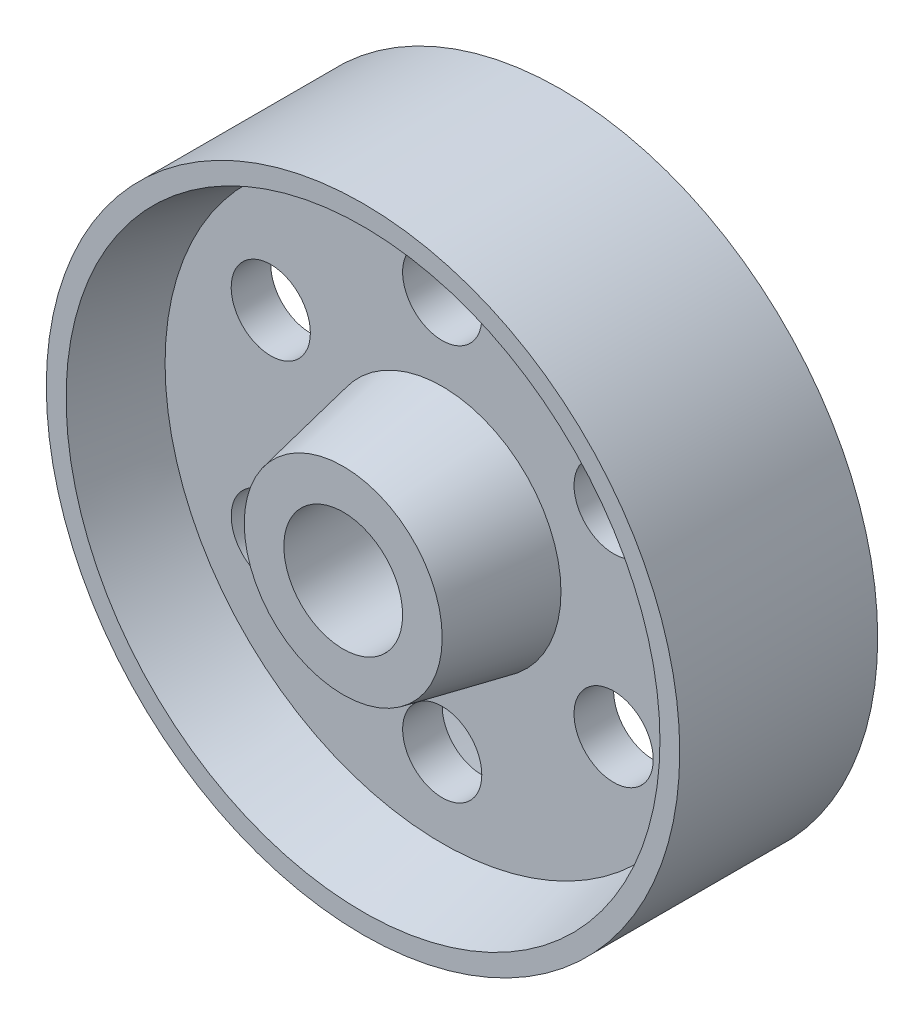
SolidWorks part; units mm, degrees
ref_plane "Front Plane" through (0, 0, 0) normal (0, 0, 1) x (1, 0, 0)
ref_plane "Top Plane" through (0, 0, 0) normal (0, 1, 0) x (1, 0, 0)
ref_plane "Right Plane" through (0, 0, 0) normal (1, 0, 0) x (0, 0, -1)
sketch "Sketch1" plane through (0, 0, 0) normal (1, 0, 0) x (0, 0, -1)
  line L0 (-37.3089, 0) -> (50.2315, 0) construction
  line L1 (0, -101.055) -> (0, 103.0597) construction
  line L2 (19.05, 9.525) -> (-19.05, 9.525)
  line L3 (-19.05, 9.525) -> (-19.05, 15.875)
  line L4 (-19.05, 15.875) -> (-3.175, 19.05)
  line L5 (-3.175, 19.05) -> (-3.175, 44.45)
  line L6 (-3.175, 44.45) -> (-15.875, 47.625)
  line L7 (-15.875, 47.625) -> (-15.875, 50.8)
  line L8 (-15.875, 50.8) -> (15.875, 50.8)
  line L9 (15.875, 47.625) -> (15.875, 50.8)
  line L10 (3.175, 44.45) -> (15.875, 47.625)
  line L11 (3.175, 19.05) -> (3.175, 44.45)
  line L12 (19.05, 15.875) -> (3.175, 19.05)
  line L13 (19.05, 9.525) -> (19.05, 15.875)
  line L14 (19.05, -9.525) -> (19.05, -15.875)
  line L15 (19.05, -15.875) -> (3.175, -19.05)
  line L16 (3.175, -19.05) -> (3.175, -44.45)
  line L17 (3.175, -44.45) -> (15.875, -47.625)
  line L18 (15.875, -47.625) -> (15.875, -50.8)
  line L19 (-15.875, -50.8) -> (15.875, -50.8)
  line L20 (-15.875, -47.625) -> (-15.875, -50.8)
  line L21 (-3.175, -44.45) -> (-15.875, -47.625)
  line L22 (-3.175, -19.05) -> (-3.175, -44.45)
  line L23 (-19.05, -15.875) -> (-3.175, -19.05)
  line L24 (-19.05, -9.525) -> (-19.05, -15.875)
  line L25 (19.05, -9.525) -> (-19.05, -9.525)
  point P14 (0, 50.8)
  point P19 (0, 9.525)
  point P31 (0, -9.525)
  point P32 (0, -50.8)
  dimension "D1" = 31.75
  dimension "D2" = 38.1
  dimension "D3" = 101.6
  dimension "D4" = 19.05
  dimension "D5" = 31.75
  dimension "D6" = 38.1
  dimension "D7" = 88.9
  dimension "D8" = 95.25
  dimension "D9" = 6.35
revolve "Revolve1" add sketch "Sketch1" angle 360 about L0
sketch "Sketch2" plane through (0, 0, 3.175) normal (0, 0, 1) x (1, 0, 0)
  circle A0 centre (0, 31.75) radius 6.35
  dimension "D1" = 12.7
  dimension "D2" = 31.75
extrude "Cut-Extrude1" cut sketch "Sketch2" against normal through all contours A0
pattern_circular "CirPattern1" count 6 over 360 about axis through (0, 0, 0) along (0, 0, 1) of "Cut-Extrude1"
